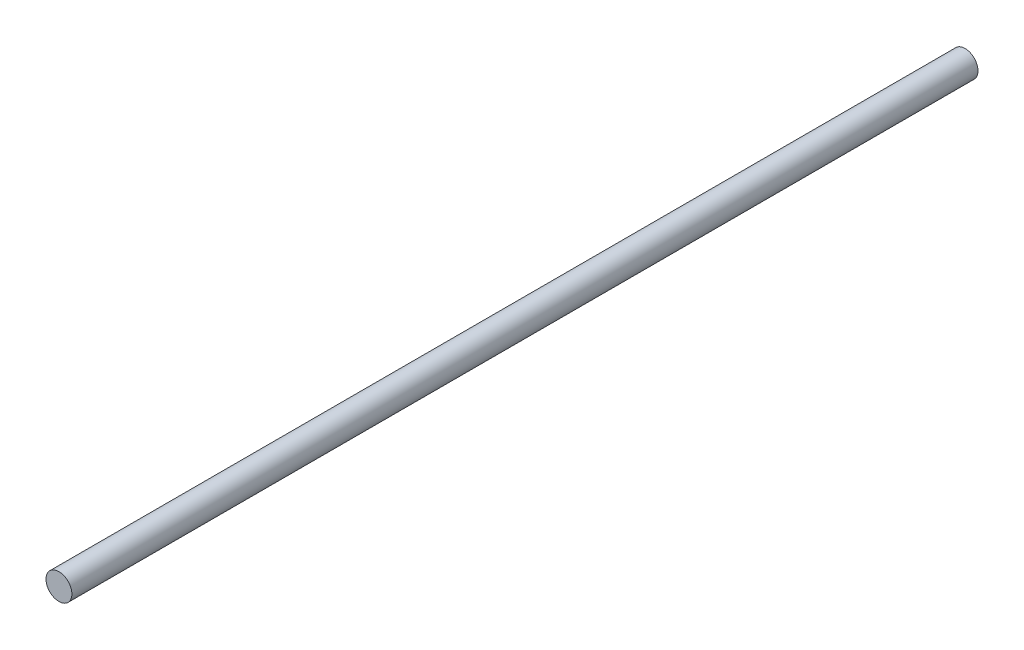
SolidWorks part; units mm, degrees
ref_plane "Front Plane" through (0, 0, 0) normal (0, 0, 1) x (1, 0, 0)
ref_plane "Top Plane" through (0, 0, 0) normal (0, 1, 0) x (1, 0, 0)
ref_plane "Right Plane" through (0, 0, 0) normal (1, 0, 0) x (0, 0, -1)
sketch "Sketch2" plane through (0, 0, 0) normal (0, 0, 1) x (1, 0, 0)
  circle A0 centre (0, 0) radius 4
  dimension "D1" = 8
extrude "Boss-Extrude1" add sketch "Sketch2" along normal blind 280
